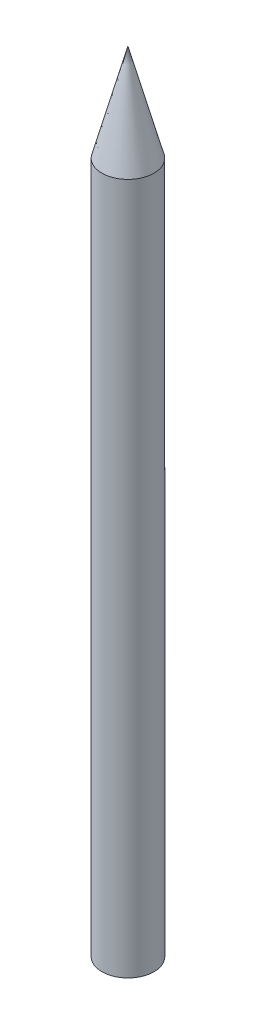
SolidWorks part; units mm, degrees
material "Nickel silver 65-12, UNS C75700"
ref_plane "Front" through (0, 0, 0) normal (0, 0, 1) x (1, 0, 0)
ref_plane "Top" through (0, 0, 0) normal (0, 1, 0) x (1, 0, 0)
ref_plane "Right" through (0, 0, 0) normal (1, 0, 0) x (0, 0, -1)
sketch "Sketch1" plane through (0, 0, 0) normal (1, 0, 0) x (0, 0, -1)
  line L12 (0, 0) -> (0, -10)
  line L13 (0, -10) -> (0.33, -10)
  line L14 (0.33, -10) -> (0.33, -1.2316)
  line L15 (0.33, -1.2316) -> (0, 0)
  dimension "D1" = 15
  dimension "D2" = 0.33
  dimension "D3" = 10
revolve "Revolve1" add sketch "Sketch1" angle 360 about L12
equation "\"D2@Sketch1\"=0.66/2"
